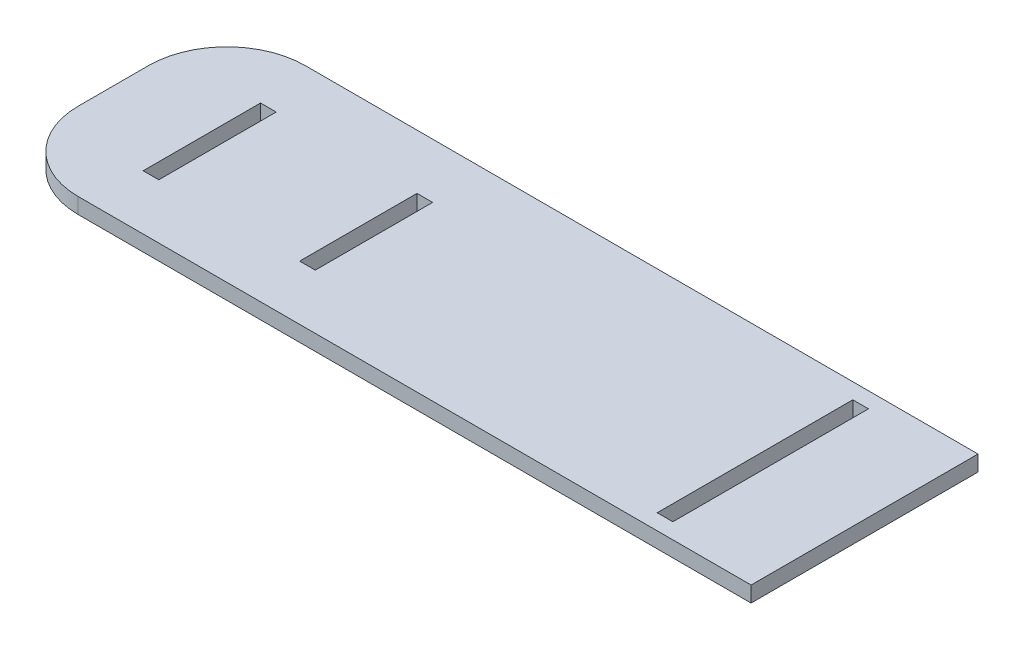
SolidWorks part; units mm, degrees
material "PTFE (general)"
ref_plane "Front Plane" through (0, 0, 0) normal (0, 0, 1) x (1, 0, 0)
ref_plane "Top Plane" through (0, 0, 0) normal (0, 1, 0) x (1, 0, 0)
ref_plane "Right Plane" through (0, 0, 0) normal (1, 0, 0) x (0, 0, -1)
sketch "Sketch1" plane through (0, 0, 0) normal (0, 1, 0) x (1, 0, 0)
  line L0 (0, 145) -> (-960, 145)
  line L1 (-960, 145) -> (-960, -145)
  line L2 (-960, -145) -> (0, -145)
  line L3 (0, -145) -> (0, 145)
  point P2 (0, 0)
  dimension "D1" = 960
  dimension "D2" = 290
extrude "Boss-Extrude1" add sketch "Sketch1" along normal blind 20
fillet "Fillet1" radius 100 2 edges at (-960, 10, -145) (-960, 10, 145)
sketch "Sketch5" plane through (0, 0, 0) normal (0, -1, 0) x (1, 0, 0)
  line L0 (-120, 125) -> (-140, 125)
  line L1 (-140, 125) -> (-140, -125)
  line L2 (-140, -125) -> (-120, -125)
  line L3 (-120, -125) -> (-120, 125)
  line L4 (0, 145) -> (0, -145) construction
  line L9 (-647, 75) -> (-627, 75)
  line L10 (-627, 75) -> (-627, -75)
  line L11 (-627, -75) -> (-647, -75)
  line L12 (-647, -75) -> (-647, 75)
  line L17 (-827, 75) -> (-847, 75)
  line L18 (-847, 75) -> (-847, -75)
  line L19 (-847, -75) -> (-827, -75)
  line L20 (-827, -75) -> (-827, 75)
  point P3 (-120, 0)
  point P10 (-627, 0)
  point P15 (-827, 0)
  point P18 (-647, 0)
  dimension "D1" = 250
  dimension "D2" = 20
  dimension "D3" = 120
  dimension "D4" = 20
  dimension "D5" = 150
  dimension "D6" = 507
  dimension "D7" = 200
extrude "Cut-Extrude1" cut sketch "Sketch5" against normal up to surface (20 mm away) up to face at (-613.5702, 20, 0)
